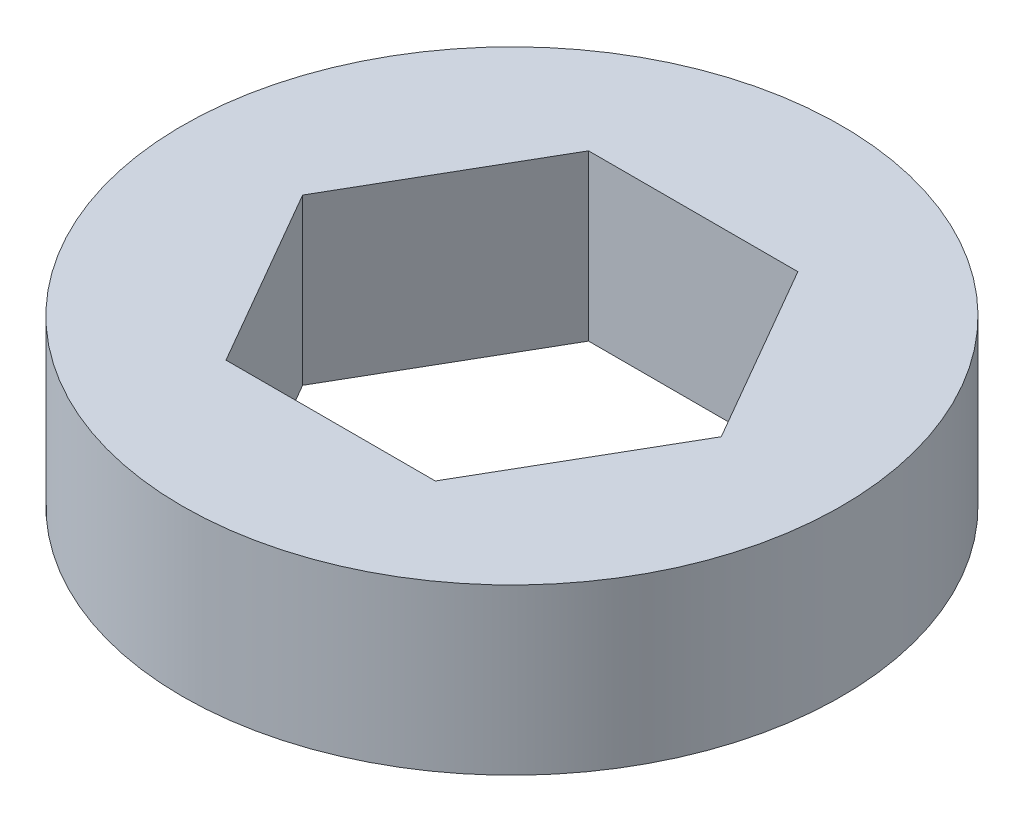
SolidWorks part; units mm, degrees
ref_plane "Ön Düzlem" through (0, 0, 0) normal (0, 0, 1) x (1, 0, 0)
ref_plane "Üst Düzlem" through (0, 0, 0) normal (0, 1, 0) x (1, 0, 0)
ref_plane "Sağ Düzlem" through (0, 0, 0) normal (1, 0, 0) x (0, 0, -1)
sketch "Sketch1" plane through (0, 0, 0) normal (0, 1, 0) x (1, 0, 0)
  line L1 (12.7017, 0) -> (6.3509, 11)
  line L2 (6.3509, 11) -> (-6.3509, 11)
  line L3 (-6.3509, 11) -> (-12.7017, 0)
  line L4 (-12.7017, 0) -> (-6.3509, -11)
  line L5 (-6.3509, -11) -> (6.3509, -11)
  line L6 (6.3509, -11) -> (12.7017, 0)
  circle A0 centre (0, 0) radius 11 construction
  circle A1 centre (0, 0) radius 20
  dimension "D2" = 40
  dimension "D1" = 22
extrude "Boss-Extrude1" add sketch "Sketch1" along normal blind 10
